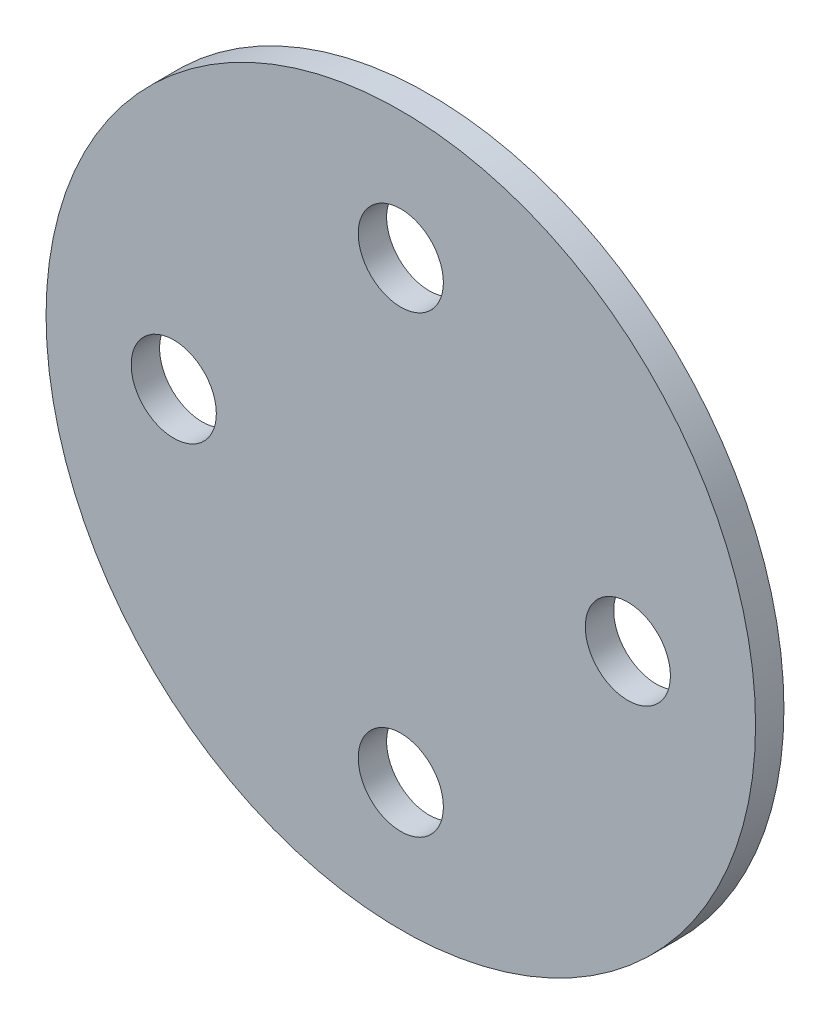
SolidWorks part; units mm, degrees
ref_plane "Ebene vorne" through (0, 0, 0) normal (0, 0, 1) x (1, 0, 0)
ref_plane "Ebene oben" through (0, 0, 0) normal (0, 1, 0) x (1, 0, 0)
ref_plane "Ebene rechts" through (0, 0, 0) normal (1, 0, 0) x (0, 0, -1)
sketch "Skizze1" plane through (0, 0, 0) normal (0, 0, 1) x (1, 0, 0)
  circle A0 centre (0, 0) radius 12.5
  circle A1 centre (0, 0) radius 9.5
  circle A2 centre (8, 0) radius 1.5
  circle A3 centre (0, -8) radius 1.5
  circle A4 centre (-8, 0) radius 1.5
  circle A5 centre (0, 8) radius 1.5
  point P15 (0, 0)
  dimension "D1" = 25
  dimension "D2" = 19
  dimension "D3" = 4
extrude "Aufsatz-Linear austragen1" add sketch "Skizze1" along normal blind 1 contours A0 A1 | A1 A5 A4 A3 A2
